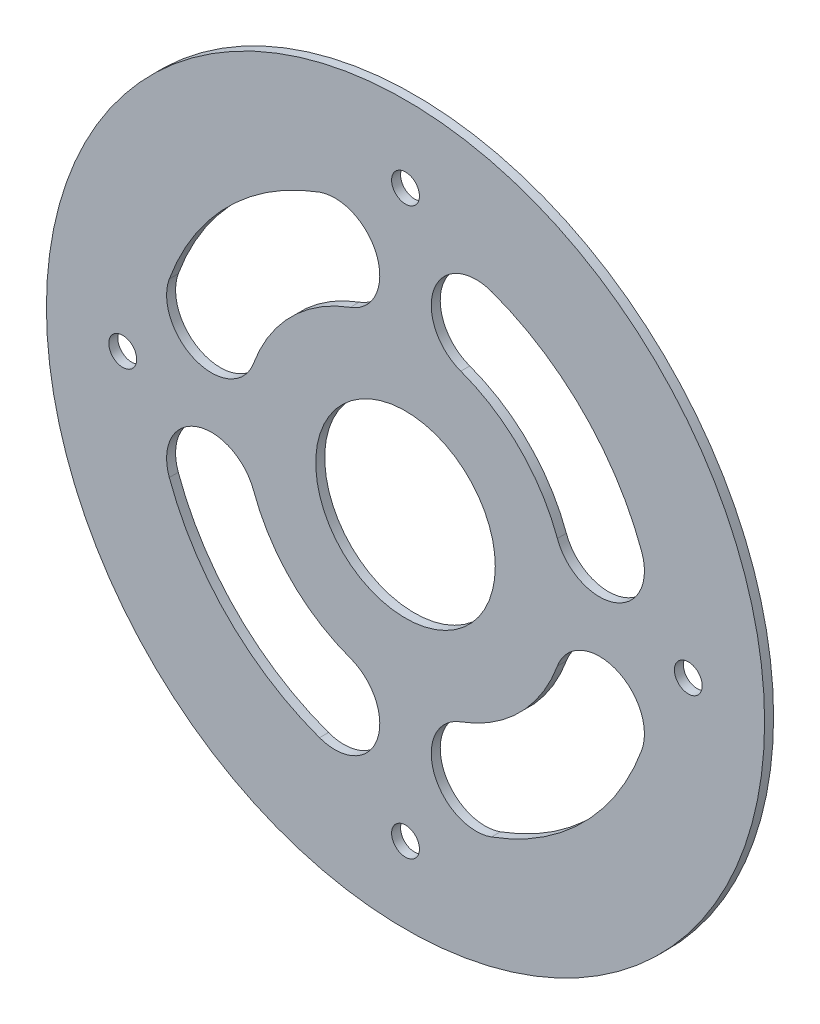
SolidWorks part; units mm, degrees
material "Thornel Mat VMA"
ref_plane "前视基准面" through (0, 0, 0) normal (0, 0, 1) x (1, 0, 0)
ref_plane "上视基准面" through (0, 0, 0) normal (0, 1, 0) x (1, 0, 0)
ref_plane "右视基准面" through (0, 0, 0) normal (1, 0, 0) x (0, 0, -1)
sketch "草图1" plane through (0, 0, 0) normal (0, 0, 1) x (1, 0, 0)
  circle A0 centre (0, 0) radius 40
  dimension "D1" = 80
extrude "凸台-拉伸1" add sketch "草图1" along normal blind 1
sketch "草图2" plane through (0, 0, 1) normal (0, 0, 1) x (1, 0, 0)
  circle A0 centre (0, 0) radius 31.5 construction
  circle A1 centre (0, 31.5) radius 1.55
  circle A2 centre (-31.5, 0) radius 1.55
  circle A3 centre (0, -31.5) radius 1.55
  circle A4 centre (31.5, 0) radius 1.55
  dimension "D1" = 63
  dimension "D2" = 3.1
extrude "切除-拉伸1" cut sketch "草图2" against normal blind 1
sketch "草图3" [suppressed] plane through (0, 0, 1) normal (0, 0, 1) x (1, 0, 0)
  line L0 (0, 27.5) -> (0, 0)
  line L1 (0, 0) -> (27.5, 0)
  arc A0 (0, 27.5) -> (3.4184, 29.4229) centre (0, 31.5) ccw
  arc A3 (29.4229, 3.4184) -> (27.5, 0) centre (31.5, 0) ccw
  arc A4 (30.7982, 6.612) -> (6.612, 30.7982) centre (0, 0) ccw
  arc A5 (30.7982, 6.612) -> (29.4229, 3.4184) centre (27.8651, 5.9823) cw
  arc A6 (6.612, 30.7982) -> (3.4184, 29.4229) centre (5.9823, 27.8651) ccw
  circle A7 centre (31.5, 0) radius 1.55 construction
  circle A8 centre (0, 31.5) radius 1.55 construction
  circle A9 centre (0, 0) radius 40 construction
  dimension "D1" = 4
  dimension "D2" = 31.5
  dimension "D3" = 3
  dimension "D4" = 4
extrude "切除-拉伸2" [suppressed] cut sketch "草图3" against normal blind 1
pattern_circular "阵列(圆周)1" [suppressed] count 4 over 360
sketch "草图4" plane through (0, 0, 1) normal (0, 0, 1) x (1, 0, 0)
  circle A0 centre (0, 0) radius 10
  dimension "D1" = 20
extrude "切除-拉伸3" cut sketch "草图4" against normal blind 1
sketch "草图5" plane through (0, 0, 1) normal (0, 0, 1) x (1, 0, 0)
  line L0 (0, 0) -> (0, -31.5) construction
  line L1 (0, 0) -> (7.8665, -21.6129) construction
  line L2 (0, 0) -> (16.2635, -16.2635) construction
  line L3 (0, 0) -> (21.6129, -7.8665) construction
  line L4 (0, 0) -> (31.5, 0) construction
  arc A0 (7.8665, -21.6129) -> (21.6129, -7.8665) centre (0, 0) ccw construction
  arc A1 (9.5766, -26.3114) -> (26.3114, -9.5766) centre (0, 0) ccw
  arc A2 (6.1564, -16.9145) -> (16.9145, -6.1564) centre (0, 0) ccw
  arc A3 (6.1564, -16.9145) -> (9.5766, -26.3114) centre (7.8665, -21.6129) ccw
  arc A4 (26.3114, -9.5766) -> (16.9145, -6.1564) centre (21.6129, -7.8665) ccw
  point P4 (16.2635, -16.2635)
  dimension "D3" = 23
  dimension "D4" = 5
  dimension "D1" = 20
  dimension "D2" = 20
extrude "切除-拉伸4" cut sketch "草图5" against normal blind 1
pattern_circular "阵列(圆周)2" count 4 over 360 about axis through (0, 0, 0) along (0, 0, 1) of "切除-拉伸4"
